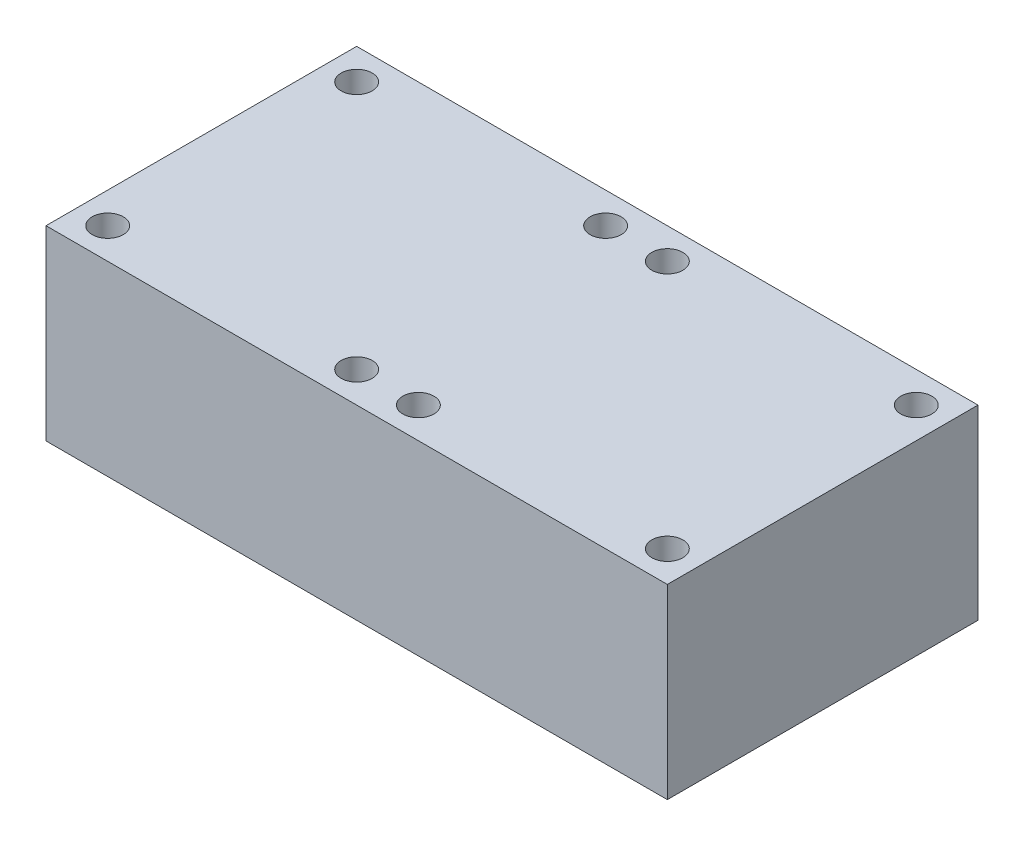
SolidWorks part; units mm, degrees
ref_plane "Front" through (0, 0, 0) normal (0, 0, 1) x (1, 0, 0)
ref_plane "Top" through (0, 0, 0) normal (0, 1, 0) x (1, 0, 0)
ref_plane "Right" through (0, 0, 0) normal (1, 0, 0) x (0, 0, -1)
sketch "草图1" plane through (0, 0, 0) normal (0, 0, 1) x (1, 0, 0)
  line L1 (-30, -15) -> (30, -15)
  line L2 (-30, -15) -> (-30, 15)
  line L3 (-30, 15) -> (30, 15)
  line L4 (30, -15) -> (30, 15)
  line L5 (0, 15) -> (0, -15) construction
  line L6 (-30, 0) -> (30, 0) construction
  point P0 (0, 0)
  dimension "D1" = 60
  dimension "D2" = 30
extrude "凸台-拉伸1" add sketch "草图1" along normal blind 30
sketch "草图2" plane through (0, -15, 0) normal (0, -1, 0) x (1, 0, 0)
  line L4 (-30, 0) -> (30, 0)
  line L5 (30, 0) -> (30, 30)
  line L6 (30, 30) -> (-30, 30)
  line L7 (-30, 30) -> (-30, 0)
  line L8 (-30, 0) -> (30, 0)
  line L9 (30, 0) -> (30, 30)
  line L10 (30, 30) -> (-30, 30)
  line L11 (-30, 30) -> (-30, 0)
  dimension "D1" = 0
extrude "切除-拉伸1" cut sketch "草图2" against normal blind 12
sketch "草图3" plane through (0, 15, 0) normal (0, 1, 0) x (1, 0, 0)
  line L0 (-30, -30) -> (0, 0) construction
  line L1 (0, 0) -> (30, -30) construction
  line L2 (-30, 0) -> (0, -30) construction
  line L3 (30, -30) -> (-30, -30) construction
  line L4 (0, -30) -> (30, 0) construction
  line L5 (0, 0) -> (0, -30) construction
  line L6 (-27.0208, -27.0208) -> (-2.9792, -27.0208) construction
  line L7 (-27.0208, -27.0208) -> (-27.0208, -2.9792) construction
  line L8 (-27.0208, -2.9792) -> (-2.9792, -2.9792) construction
  line L9 (-2.9792, -27.0208) -> (-2.9792, -2.9792) construction
  line L10 (-15, -2.9792) -> (-15, -27.0208) construction
  line L11 (-27.0208, -15) -> (-2.9792, -15) construction
  circle A0 centre (-27.0208, -2.9792) radius 1.5
  circle A1 centre (-2.9792, -2.9792) radius 1.5
  circle A2 centre (-2.9792, -27.0208) radius 1.5
  circle A3 centre (-27.0208, -27.0208) radius 1.5
  circle A4 centre (27.0208, -27.0208) radius 1.5
  circle A5 centre (2.9792, -27.0208) radius 1.5
  circle A6 centre (2.9792, -2.9792) radius 1.5
  circle A7 centre (27.0208, -2.9792) radius 1.5
  point P11 (-15, -15)
  dimension "D1" = 3
  dimension "D2" = 34
extrude "切除-拉伸2" cut sketch "草图3" against normal through all
